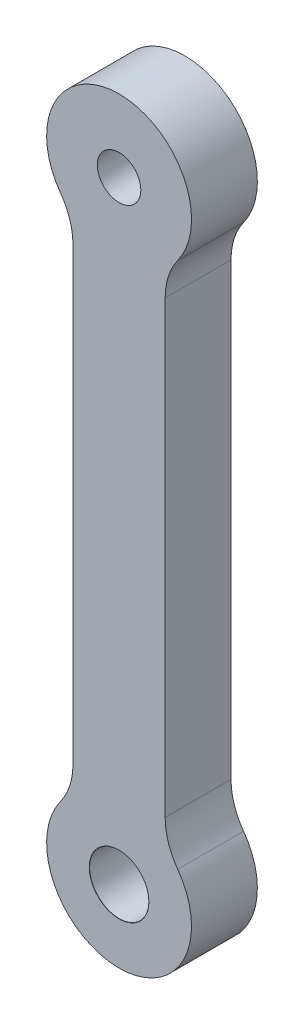
SolidWorks part; units mm, degrees
ref_plane "Plan de face" through (0, 0, 0) normal (0, 0, 1) x (1, 0, 0)
ref_plane "Plan de dessus" through (0, 0, 0) normal (0, 1, 0) x (1, 0, 0)
ref_plane "Plan de droite" through (0, 0, 0) normal (1, 0, 0) x (0, 0, -1)
sketch "Esquisse1" plane through (0, 0, 0) normal (0, 0, 1) x (1, 0, 0)
  line L0 (0, 21.7205) -> (0, -6.0998) construction
  line L1 (-7, 38) -> (-7, -38)
  line L2 (7, 38) -> (7, -38)
  line L3 (-8.714, 0) -> (6.1966, 0) construction
  arc A0 (7, 38) -> (-7, 38) centre (0, 46.4853) ccw
  arc A1 (7, -38) -> (-7, -38) centre (0, -46.4853) cw
  dimension "D3" = 11
  dimension "D1" = 76
  dimension "D2" = 14
extrude "Boss.-Extru.2" add sketch "Esquisse1" along normal blind 10
sketch "Esquisse2" plane through (0, 0, 0) normal (0, 0, -1) x (-1, 0, 0)
  circle A0 centre (0, 46.4853) radius 4.95
  arc A1 (7, 38) -> (-7, 38) centre (0, 46.4853) ccw construction
  dimension "D1" = 9.9
fillet "Congé1" radius 10 4 edges at (7, 38, 5) (7, -38, 5) (-7, -38, 5) (-7, 38, 5)
sketch "Esquisse5" plane through (0, 0, 10) normal (0, 0, 1) x (1, 0, 0)
  point P0 (0, -46.4853)
hole_wizard "Dégagement M81" positions "Esquisse5" profile "Esquisse4" hole size "M8" standard "ISO" end condition up to next
sketch "Esquisse4" plane through (0, -46.4853, 10) normal (1, 0, 0) x (0, -1, 0)
  line L0 (0, 0) -> (0, 10)
  line L1 (0, 10) -> (4.5, 10)
  line L2 (4.5, 10) -> (4.5, 0.025)
  line L3 (4.5, 0.025) -> (4.525, 0)
  line L5 (4.525, 0) -> (0, 0)
  line L6 (-4.5, 0.025) -> (-4.525, 0) construction
  line L11 (0, -6.35) -> (0, 107.95) construction
  dimension "Diamètre du perçage jusqu'au prochain" = 9
  dimension "Profondeur du perçage jusqu'au prochain" = 10
  dimension "Diamètre du fraisage entrant" = 9.05
  dimension "Angle du fraisage entrant" = 90
sketch "Esquisse8" plane through (0, 0, 10) normal (0, 0, 1) x (1, 0, 0)
  point P0 (0, 46.4853)
hole_wizard "Dégagement M61" positions "Esquisse8" profile "Esquisse7" hole size "M6" standard "ISO" end condition through all
sketch "Esquisse7" plane through (0, 46.4853, 10) normal (1, 0, 0) x (0, -1, 0)
  line L0 (0, 0) -> (0, 10)
  line L1 (0, 10) -> (3.3, 10)
  line L2 (3.3, 10) -> (3.3, 0)
  line L5 (3.3, 0) -> (0, 0)
  line L11 (0, -6.35) -> (0, 107.95) construction
  dimension "Diamètre du perçage jusqu'au prochain" = 6.6
  dimension "Profondeur du perçage jusqu'au prochain" = 10
equation "\"L2\" = 76mm"
equation "\"D1@Esquisse1\"=\"L2\""
